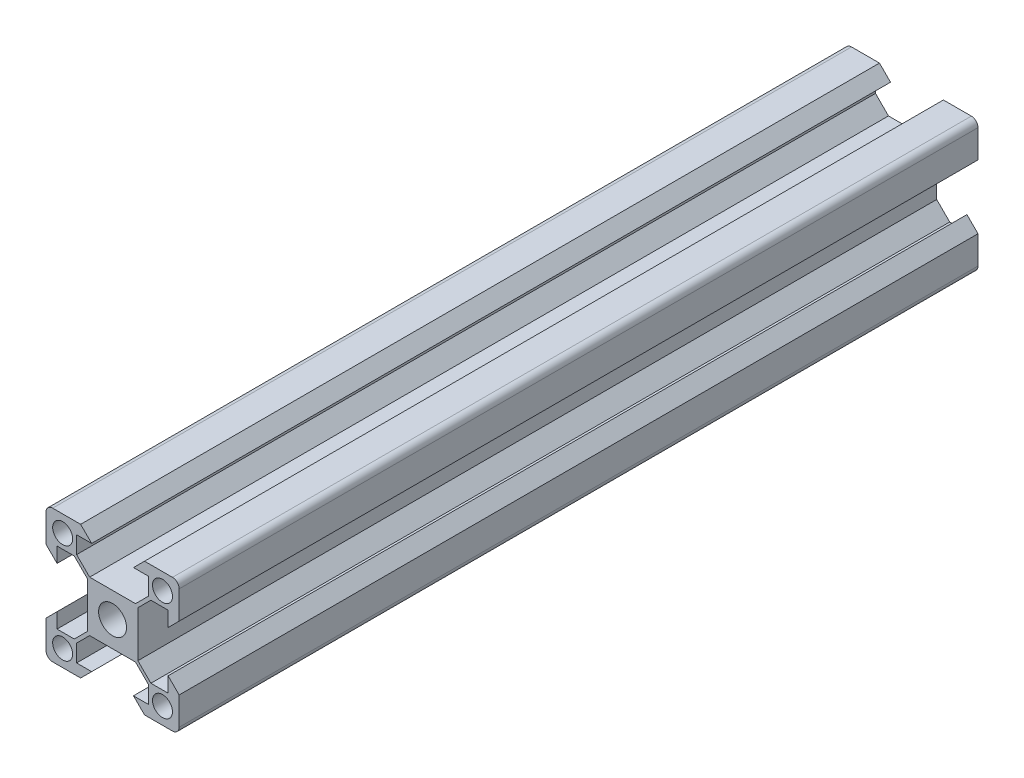
SolidWorks part; units mm, degrees
material "铝管"
ref_plane "前视基准面" through (0, 0, 0) normal (0, 0, 1) x (1, 0, 0)
ref_plane "上视基准面" through (0, 0, 0) normal (0, 1, 0) x (1, 0, 0)
ref_plane "右视基准面" through (0, 0, 0) normal (1, 0, 0) x (0, 0, -1)
sketch "草图1" plane through (0, 0, 0) normal (0, 0, 1) x (1, 0, 0)
  line L0 (0, 0) -> (-40.5659, 40.5659) construction
  line L1 (0, 0) -> (0, 75.5033) construction
  line L2 (-10, 10) -> (-10, 4.8)
  line L3 (-10, 4.8) -> (-8.34, 3.14)
  line L4 (-8.34, 3.14) -> (-8.34, 5.4)
  line L5 (-5.7536, 5.4) -> (-3.8, 3.4464)
  line L6 (-3.8, 3.4464) -> (-3.8, -3.4464)
  line L7 (-3.8, 0) -> (15.6715, 0) construction
  line L8 (-5.4, 8.34) -> (-5.4, 5.7536)
  line L9 (-3.4464, 3.8) -> (3.4464, 3.8)
  line L10 (-5.4, 5.7536) -> (-3.4464, 3.8)
  line L11 (-3.14, 8.34) -> (-5.4, 8.34)
  line L12 (-8.34, 5.4) -> (-5.7536, 5.4)
  line L13 (-4.8, 10) -> (-3.14, 8.34)
  line L14 (-10, 10) -> (-4.8, 10)
  line L15 (-10, -10) -> (-4.8, -10)
  line L16 (-4.8, -10) -> (-3.14, -8.34)
  line L17 (-8.34, -5.4) -> (-5.7536, -5.4)
  line L18 (-3.14, -8.34) -> (-5.4, -8.34)
  line L19 (-5.4, -5.7536) -> (-3.4464, -3.8)
  line L20 (-3.4464, -3.8) -> (3.4464, -3.8)
  line L21 (-5.4, -8.34) -> (-5.4, -5.7536)
  line L22 (-5.7536, -5.4) -> (-3.8, -3.4464)
  line L23 (-8.34, -3.14) -> (-8.34, -5.4)
  line L24 (-10, -4.8) -> (-8.34, -3.14)
  line L25 (-10, -10) -> (-10, -4.8)
  line L26 (10, -10) -> (10, -4.8)
  line L27 (10, -4.8) -> (8.34, -3.14)
  line L28 (8.34, -3.14) -> (8.34, -5.4)
  line L29 (5.7536, -5.4) -> (3.8, -3.4464)
  line L30 (5.4, -8.34) -> (5.4, -5.7536)
  line L31 (5.4, -5.7536) -> (3.4464, -3.8)
  line L32 (3.14, -8.34) -> (5.4, -8.34)
  line L33 (8.34, -5.4) -> (5.7536, -5.4)
  line L34 (4.8, -10) -> (3.14, -8.34)
  line L35 (10, -10) -> (4.8, -10)
  line L36 (10, 10) -> (4.8, 10)
  line L37 (4.8, 10) -> (3.14, 8.34)
  line L38 (8.34, 5.4) -> (5.7536, 5.4)
  line L39 (3.14, 8.34) -> (5.4, 8.34)
  line L40 (5.4, 5.7536) -> (3.4464, 3.8)
  line L41 (5.4, 8.34) -> (5.4, 5.7536)
  line L42 (3.8, 3.4464) -> (3.8, -3.4464)
  line L43 (5.7536, 5.4) -> (3.8, 3.4464)
  line L44 (8.34, 3.14) -> (8.34, 5.4)
  line L45 (10, 4.8) -> (8.34, 3.14)
  line L46 (10, 10) -> (10, 4.8)
  circle A0 centre (-7.5, 7.5) radius 1.5
  circle A1 centre (0, 0) radius 2.1
  circle A2 centre (-7.5, -7.5) radius 1.5
  circle A3 centre (7.5, -7.5) radius 1.5
  circle A4 centre (7.5, 7.5) radius 1.5
  point P54 (0, -3.8)
  point P64 (0, 3.8)
  dimension "D6" = 3
  dimension "D7" = 7.5
  dimension "D9" = 4.2
  dimension "D1" = 45
  dimension "D2" = 4.8
  dimension "D3" = 3.8
  dimension "D4" = 10
  dimension "D5" = 5.4
  dimension "D8" = 3.14
  dimension "D10" = 10
  dimension "D11" = 0.5
extrude "凸台-拉伸1" add sketch "草图1" along normal mid plane 120
fillet "圆角1" radius 1 4 edges at (-10, -10, 0) (10, -10, 0) (-10, 10, 0) (10, 10, 0)
